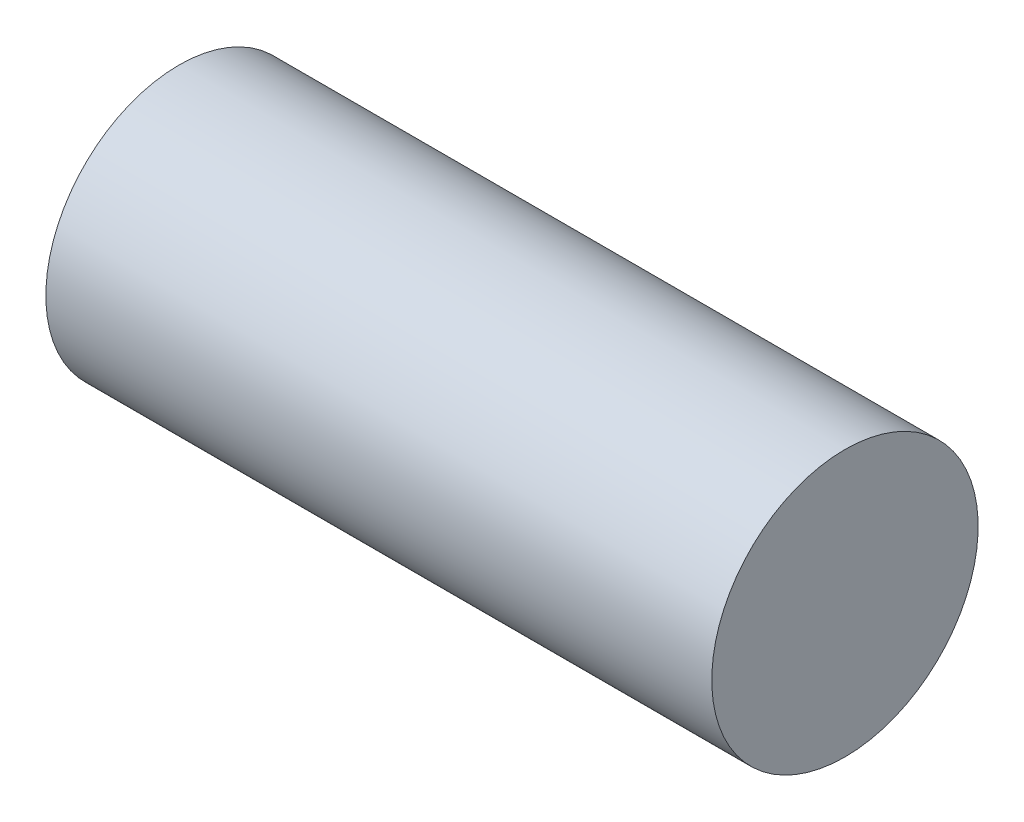
SolidWorks part; units mm, degrees
ref_plane "Front Plane" through (0, 0, 0) normal (0, 0, 1) x (1, 0, 0)
ref_plane "Top Plane" through (0, 0, 0) normal (0, 1, 0) x (1, 0, 0)
ref_plane "Right Plane" through (0, 0, 0) normal (1, 0, 0) x (0, 0, -1)
sketch "Sketch1" plane through (0, 0, 0) normal (0, 0, 1) x (1, 0, 0)
  line L0 (0, 0) -> (50, 0) construction
  line L1 (0, 0) -> (0, 5)
  line L2 (0, 5) -> (25, 5)
  line L3 (25, 5) -> (25, 0)
  line L4 (25, 0) -> (0, 0)
revolve "Revolve1" add sketch "Sketch1" angle 360 about L0
